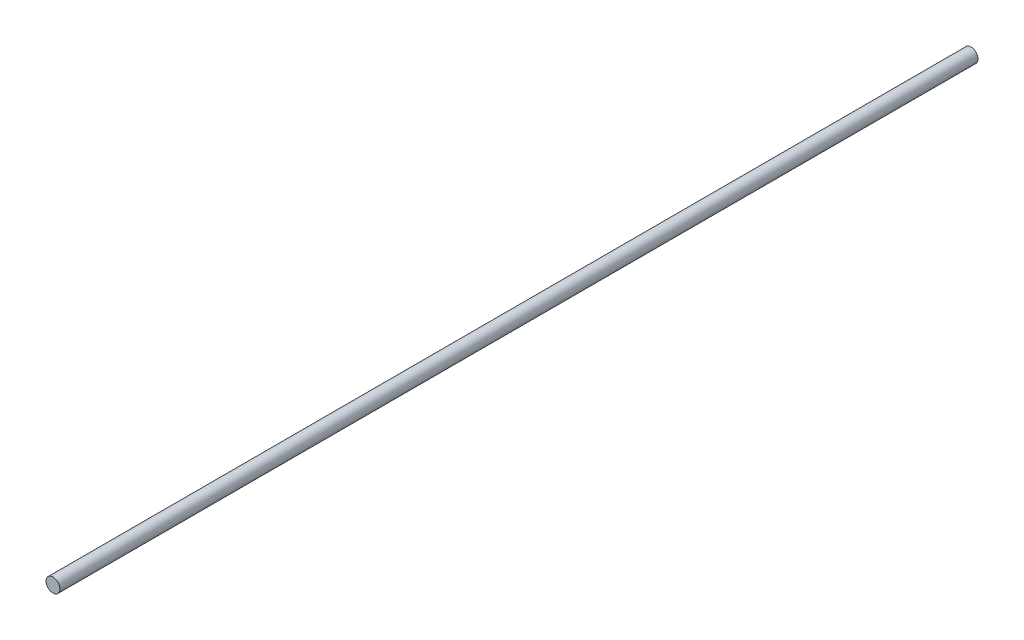
SolidWorks part; units mm, degrees
material "7075-T6 (SN)"
ref_plane "Front Plane" through (0, 0, 0) normal (0, 0, 1) x (1, 0, 0)
ref_plane "Top Plane" through (0, 0, 0) normal (0, 1, 0) x (1, 0, 0)
ref_plane "Right Plane" through (0, 0, 0) normal (1, 0, 0) x (0, 0, -1)
sketch "Sketch1" plane through (0, 0, 0) normal (0, 0, 1) x (1, 0, 0)
  circle A0 centre (0, 0) radius 1.7
  dimension "D1" = 3.4
extrude "Boss-Extrude1" add sketch "Sketch1" along normal blind 210
ref_plane "Plane1" through (0, 0, 105) normal (0, 0, -1) x (-1, 0, 0)
sketch "Sketch2" plane through (0, 0, 0) normal (0, 0, -1) x (-1, 0, 0)
  circle A0 centre (0, 0) radius 1.7 construction
  circle A1 centre (0, 0) radius 1.7
extrude "Boss-Extrude2" add sketch "Sketch2" along normal blind 15
